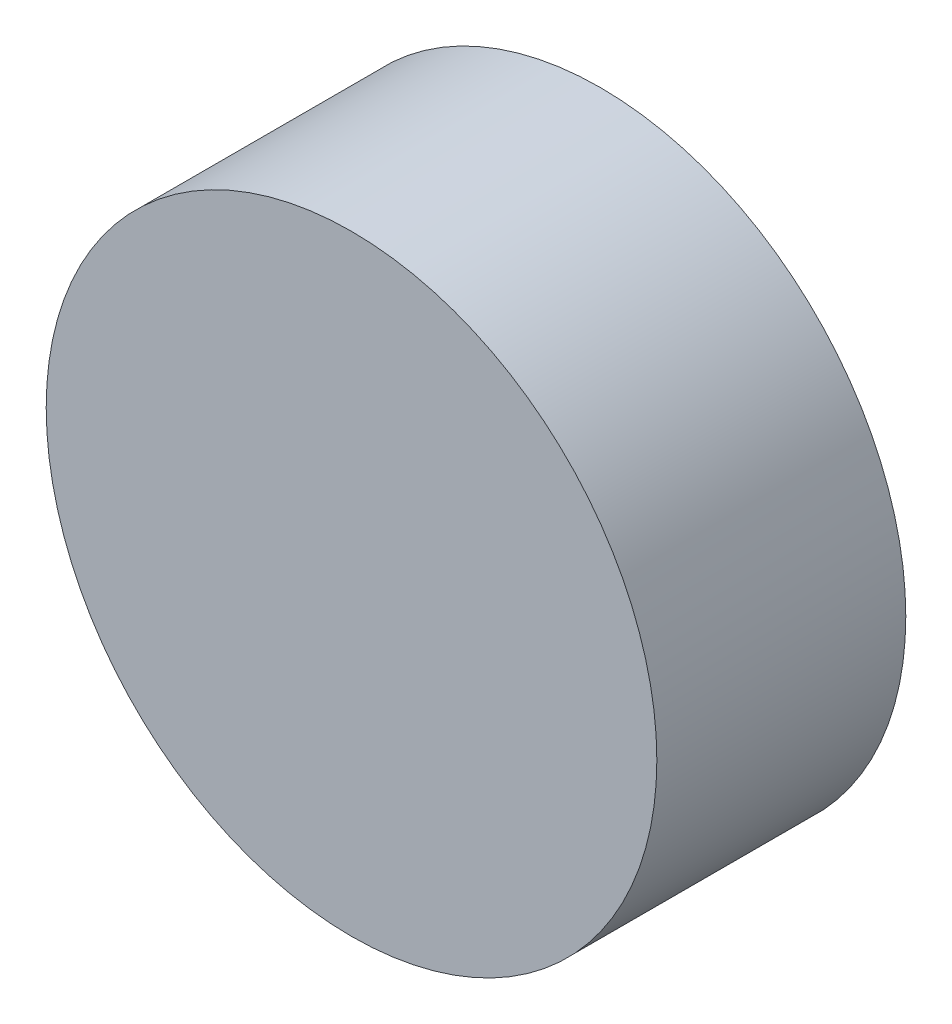
SolidWorks part; units mm, degrees
ref_plane "前视基准面" through (0, 0, 0) normal (0, 0, 1) x (1, 0, 0)
ref_plane "上视基准面" through (0, 0, 0) normal (0, 1, 0) x (1, 0, 0)
ref_plane "右视基准面" through (0, 0, 0) normal (1, 0, 0) x (0, 0, -1)
other "Configuration Table"
sketch "草图1" plane through (0, 0, 0) normal (0, 0, 1) x (1, 0, 0)
  circle A0 centre (0, 0) radius 32.5
  dimension "D1" = 65
extrude "凸台-拉伸1" add sketch "草图1" along normal blind 26.5
